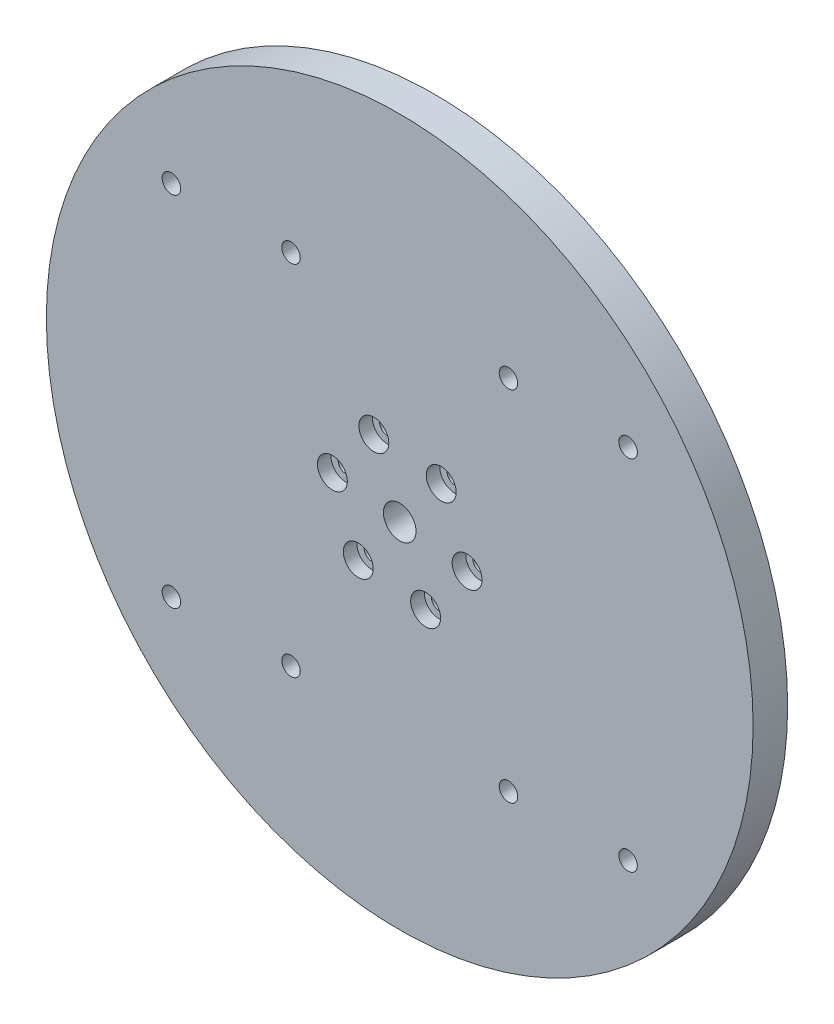
SolidWorks part; units mm, degrees
material "Aleación 6061"
ref_plane "Alzado" through (0, 0, 0) normal (0, 0, 1) x (1, 0, 0)
ref_plane "Planta" through (0, 0, 0) normal (0, 1, 0) x (1, 0, 0)
ref_plane "Vista lateral" through (0, 0, 0) normal (1, 0, 0) x (0, 0, -1)
sketch "Sk_Disco" plane through (0, 0, 0) normal (0, 0, 1) x (1, 0, 0)
  circle A0 centre (0, 0) radius 65
  dimension "D1" = 130
extrude "Disco" add sketch "Sk_Disco" along normal blind 6.35 from offset 70
sketch "Sk_Centrador_arandela_eje_51110" plane through (0, 0, 0) normal (0, 0, 1) x (1, 0, 0)
  circle A0 centre (0, 0) radius 24.9
  circle A1 centre (0, 0) radius 23
  dimension "D1" = 49.8
  dimension "D2" = 46
extrude "Centrador_arandela_eje_51110" add sketch "Sk_Centrador_arandela_eje_51110" along normal blind 3 from offset 67
sketch "Sk_Pasantes_M2-5_rotor_J1" plane through (0, 0, 0) normal (0, 0, 1) x (1, 0, 0)
  circle A0 centre (12.3902, -1.6532) radius 1.45
  circle A1 centre (7.6268, 9.9036) radius 1.45
  circle A2 centre (-4.7634, 11.5568) radius 1.45
  circle A3 centre (-12.3902, 1.6532) radius 1.45
  circle A4 centre (-7.6268, -9.9036) radius 1.45
  circle A5 centre (4.7634, -11.5568) radius 1.45
  dimension "D1" = 2.9
  dimension "D4" = 2.9
  dimension "D7" = 2.9
  dimension "D10" = 2.9
  dimension "D13" = 2.9
  dimension "D16" = 2.9
  dimension "D2" = 12.3902
  dimension "D3" = 1.6532
  dimension "D5" = 7.6268
  dimension "D6" = 9.9036
  dimension "D8" = 4.7634
  dimension "D9" = 11.5568
  dimension "D11" = 12.3902
  dimension "D12" = 1.6532
  dimension "D14" = 7.6268
  dimension "D15" = 9.9036
  dimension "D17" = 4.7634
  dimension "D18" = 11.5568
extrude "Pasantes_M2-5_rotor_J1" cut sketch "Sk_Pasantes_M2-5_rotor_J1" along normal blind 6.35 from offset 70
sketch "Sk_Cajas_M2-5" plane through (0, 0, 0) normal (0, 0, 1) x (1, 0, 0)
  circle A0 centre (12.3902, -1.6532) radius 2.75
  circle A1 centre (7.6268, 9.9036) radius 2.75
  circle A2 centre (-4.7634, 11.5568) radius 2.75
  circle A3 centre (-12.3902, 1.6532) radius 2.75
  circle A4 centre (-7.6268, -9.9036) radius 2.75
  circle A5 centre (4.7634, -11.5568) radius 2.75
  dimension "D1" = 5.5
  dimension "D4" = 5.5
  dimension "D7" = 5.5
  dimension "D10" = 5.5
  dimension "D13" = 5.5
  dimension "D16" = 5.5
  dimension "D2" = 12.3902
  dimension "D3" = 1.6532
  dimension "D5" = 7.6268
  dimension "D6" = 9.9036
  dimension "D8" = 4.7634
  dimension "D9" = 11.5568
  dimension "D11" = 12.3902
  dimension "D12" = 1.6532
  dimension "D14" = 7.6268
  dimension "D15" = 9.9036
  dimension "D17" = 4.7634
  dimension "D18" = 11.5568
extrude "Cajas_M2-5" cut sketch "Sk_Cajas_M2-5" along normal blind 2.5 from offset 73.85
sketch "Sk_Paso_cable" plane through (0, 0, 0) normal (0, 0, 1) x (1, 0, 0)
  circle A0 centre (0, 0) radius 3
  dimension "D1" = 6
extrude "Paso_cable" cut sketch "Sk_Paso_cable" along normal blind 6.35 from offset 70
sketch "Sk_Pasantes_M4_angulos" plane through (0, 0, 0) normal (0, 0, 1) x (1, 0, 0)
  circle A0 centre (-11, -50.86) radius 2.25
  circle A1 centre (-11, 50.86) radius 2.25
  circle A2 centre (11, -50.86) radius 2.25
  circle A3 centre (11, 50.86) radius 2.25
  dimension "D1" = 4.5
  dimension "D4" = 4.5
  dimension "D7" = 4.5
  dimension "D10" = 4.5
  dimension "D2" = 11
  dimension "D3" = 50.86
  dimension "D5" = 11
  dimension "D6" = 50.86
  dimension "D8" = 11
  dimension "D9" = 50.86
  dimension "D11" = 11
  dimension "D12" = 50.86
sketch "Sk_Pasantes_M4_paredes" plane through (0, 0, 76.35) normal (0, 0, 1) x (1, 0, 0)
  circle A0 centre (-35, -34.75) radius 2.25
  circle A1 centre (-35, 34.75) radius 2.25
  circle A2 centre (35, -34.75) radius 2.25
  circle A3 centre (35, 34.75) radius 2.25
sketch "Sk_Cajas_M4_paredes" plane through (0, 0, 70) normal (0, 0, -1) x (-1, 0, 0)
  circle A0 centre (35, -34.75) radius 4.25
  circle A1 centre (35, 34.75) radius 4.25
  circle A2 centre (-35, -34.75) radius 4.25
  circle A3 centre (-35, 34.75) radius 4.25
sketch "Sk_Pasantes_M3_paredes" plane through (0, 0, 76.35) normal (0, 0, 1) x (1, 0, 0)
  circle A0 centre (-42, -32.925) radius 1.7
  circle A1 centre (-20, -32.925) radius 1.7
  circle A2 centre (20, -32.925) radius 1.7
  circle A3 centre (42, -32.925) radius 1.7
  circle A4 centre (-42, 32.925) radius 1.7
  circle A5 centre (-20, 32.925) radius 1.7
  circle A6 centre (20, 32.925) radius 1.7
  circle A7 centre (42, 32.925) radius 1.7
extrude "Pasantes_M3_paredes" cut sketch "Sk_Pasantes_M3_paredes" against normal through all
sketch "Sk_Cajas_M3_paredes" plane through (0, 0, 70) normal (0, 0, -1) x (-1, 0, 0)
  circle A0 centre (42, -32.925) radius 3.25
  circle A1 centre (20, -32.925) radius 3.25
  circle A2 centre (-20, -32.925) radius 3.25
  circle A3 centre (-42, -32.925) radius 3.25
  circle A4 centre (42, 32.925) radius 3.25
  circle A5 centre (20, 32.925) radius 3.25
  circle A6 centre (-20, 32.925) radius 3.25
  circle A7 centre (-42, 32.925) radius 3.25
extrude "Cajas_M3_paredes" cut sketch "Sk_Cajas_M3_paredes" against normal blind 3.5
